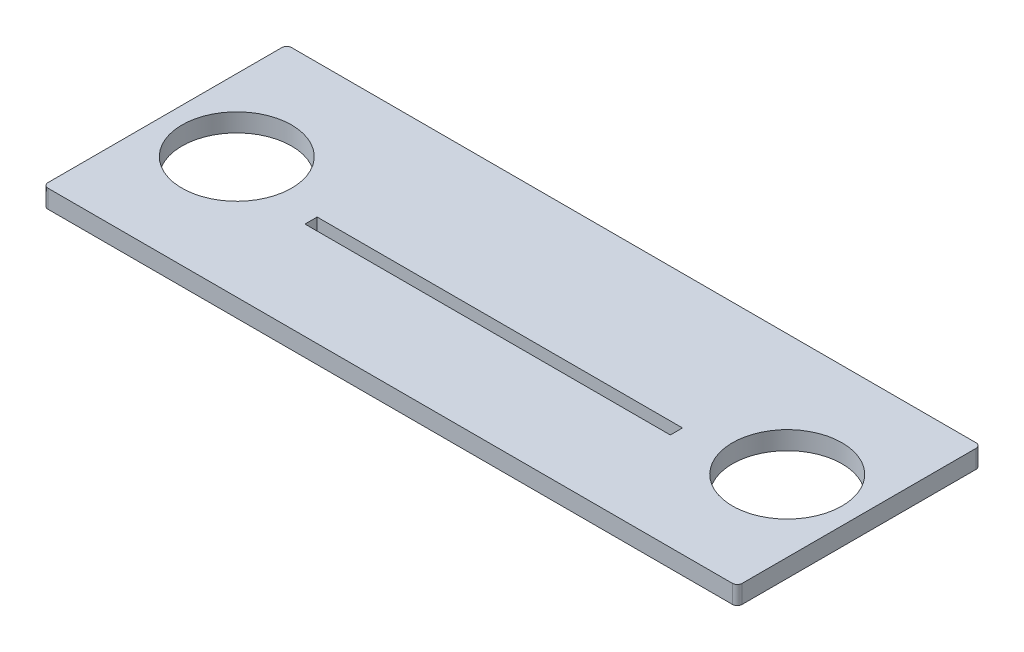
SolidWorks part; units mm, degrees
ref_plane "Front Plane" through (0, 0, 0) normal (0, 0, 1) x (1, 0, 0)
ref_plane "Top Plane" through (0, 0, 0) normal (0, 1, 0) x (1, 0, 0)
ref_plane "Right Plane" through (0, 0, 0) normal (1, 0, 0) x (0, 0, -1)
sketch "Sketch1" plane through (0, 0, 0) normal (0, 1, 0) x (1, 0, 0)
  line L1 (-142.5, -50) -> (142.5, -50)
  line L2 (-142.5, -50) -> (-142.5, 50)
  line L3 (-142.5, 50) -> (142.5, 50)
  line L4 (142.5, -50) -> (142.5, 50)
  line L5 (-142.5, -50) -> (142.5, 50) construction
  line L6 (-142.5, 50) -> (142.5, -50) construction
  point P0 (0, 0)
  dimension "D1" = 285
  dimension "D2" = 302.0348
extrude "Boss-Extrude1" add sketch "Sketch1" along normal blind 7.5
sketch "Sketch2" plane through (0, 7.5, 0) normal (0, 1, 0) x (1, 0, 0)
  line L0 (-142.5, 0) -> (-113, 0)
  line L1 (-142.5, 50) -> (-142.5, -50) construction
  line L2 (142.5, 0) -> (113, 0)
  line L3 (142.5, -50) -> (142.5, 50) construction
  line L5 (142.5, 50) -> (-142.5, 50) construction
  line L6 (-75, -10) -> (75, -10)
  line L7 (-75, -10) -> (-75, -5)
  line L8 (-75, -5) -> (75, -5)
  line L9 (75, -10) -> (75, -5)
  line L10 (-75, -10) -> (75, -5) construction
  line L11 (-75, -5) -> (75, -10) construction
  circle A0 centre (-113, 0) radius 22.5
  circle A1 centre (113, 0) radius 22.5
  point P13 (0, 0)
  dimension "D3" = 45
  dimension "D4" = 45
  dimension "D6" = 5
  dimension "D1" = 29.5
  dimension "D2" = 29.5
  dimension "D5" = 150
  dimension "D7" = 55
  dimension "D8" = 67.5
extrude "Cut-Extrude1" cut sketch "Sketch2" against normal blind 10 and the other way through all contours A1 | L7 L6 L9 L8 | A0
fillet "Fillet1" radius 2 4 edges at (142.5, 3.75, -50) (142.5, 3.75, 50) (-142.5, 3.75, 50) (-142.5, 3.75, -50)
